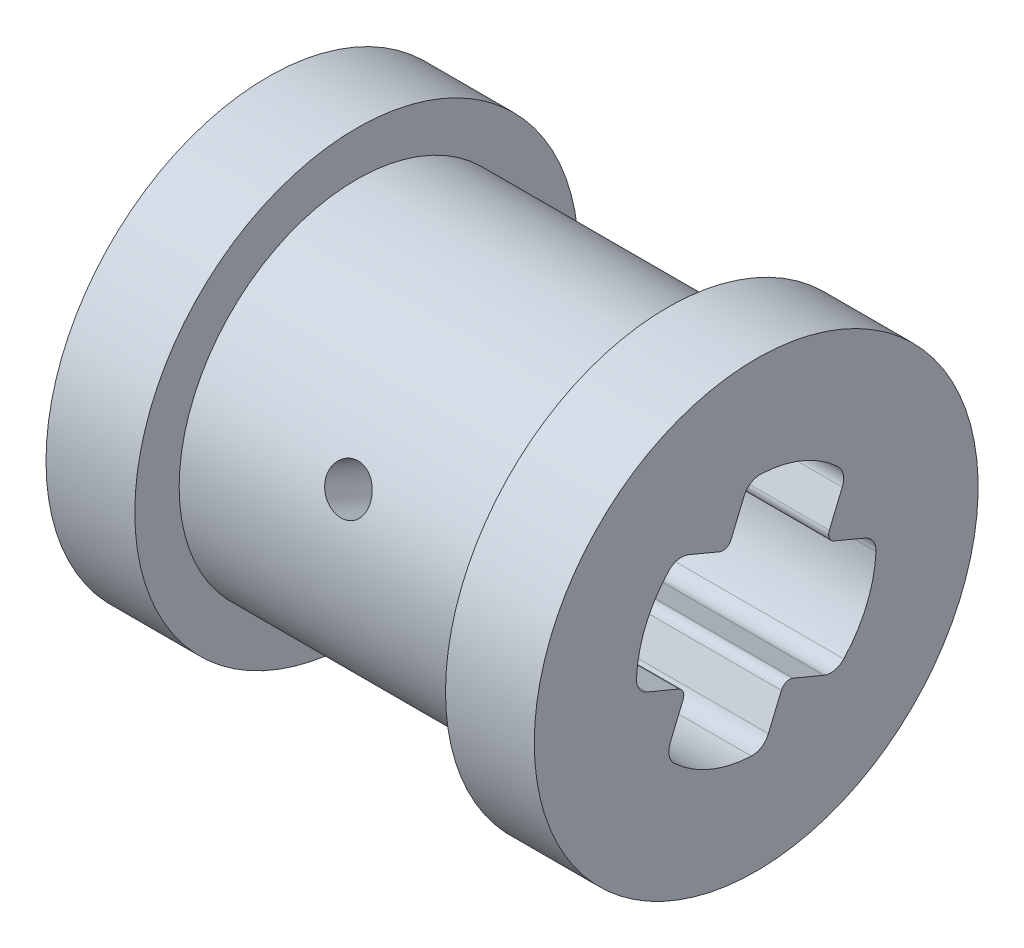
SolidWorks part; units mm, degrees
ref_plane "Front Plane" through (0, 0, 0) normal (0, 0, 1) x (1, 0, 0)
ref_plane "Top Plane" through (0, 0, 0) normal (0, 1, 0) x (1, 0, 0)
ref_plane "Right Plane" through (0, 0, 0) normal (1, 0, 0) x (0, 0, -1)
sketch "Sketch1" plane through (0, 0, 0) normal (0, 1, 0) x (1, 0, 0)
  line L0 (-3.5, -5) -> (-3.5, -4)
  line L1 (-5.5, 0) -> (5.5, 0)
  line L2 (-5.5, 0) -> (-5.5, -5)
  line L3 (-5.5, -5) -> (-3.5, -5)
  line L4 (5.5, 0) -> (5.5, -5)
  line L7 (-3.5, -4) -> (3.5, -4)
  line L8 (3.5, -4) -> (3.5, -5)
  line L9 (3.5, -5) -> (5.5, -5)
  point P10 (0, 0)
  dimension "D1" = 5
  dimension "D2" = 11
  dimension "D3" = 2
  dimension "D4" = 2
  dimension "D5" = 1
revolve "Revolve1" add sketch "Sketch1" angle 360 about L1
sketch "Sketch3" plane through (5.5, 0, 0) normal (1, 0, 0) x (0, 0, -1)
  line B0 (-1.3705, -0.9444) -> (-1.6623, -1.6422)
  line B1 (-0.0017, -2.3367) -> (0.2902, -1.6388)
  line B2 (0.9444, -1.3705) -> (1.6422, -1.6623)
  line B3 (-0.9444, 1.3705) -> (-1.6422, 1.6623)
  line B4 (-2.3367, 0.0017) -> (-1.6388, -0.2902)
  line B5 (0.0017, 2.3367) -> (-0.2902, 1.6388)
  line B6 (1.3705, 0.9444) -> (1.6623, 1.6422)
  line B7 (2.3367, -0.0017) -> (1.6388, 0.2902)
  arc B8 (-1.6623, -1.6422) -> (-1.6383, -1.7538) centre (-1.5701, -1.6808) ccw
  arc B9 (-1.6383, -1.7538) -> (-0.098, -2.398) centre (0, 0) ccw
  arc B10 (-0.098, -2.398) -> (-0.0017, -2.3367) centre (-0.0939, -2.2981) ccw
  arc B11 (1.6422, -1.6623) -> (1.7538, -1.6383) centre (1.6808, -1.5701) ccw
  arc B12 (0.9444, -1.3705) -> (0.2902, -1.6388) centre (0.7514, -1.8318) ccw
  arc B13 (-1.6422, 1.6623) -> (-1.7538, 1.6383) centre (-1.6808, 1.5701) ccw
  arc B14 (-2.398, 0.098) -> (-2.3367, 0.0017) centre (-2.2981, 0.0939) ccw
  arc B15 (-1.7538, 1.6383) -> (-2.398, 0.098) centre (0, 0) ccw
  arc B16 (-1.3705, -0.9444) -> (-1.6388, -0.2902) centre (-1.8318, -0.7514) ccw
  arc B17 (0.098, 2.398) -> (0.0017, 2.3367) centre (0.0939, 2.2981) ccw
  arc B18 (1.6383, 1.7538) -> (0.098, 2.398) centre (0, 0) ccw
  arc B19 (-0.9444, 1.3705) -> (-0.2902, 1.6388) centre (-0.7514, 1.8318) ccw
  arc B20 (1.6623, 1.6422) -> (1.6383, 1.7538) centre (1.5701, 1.6808) ccw
  arc B21 (1.3705, 0.9444) -> (1.6388, 0.2902) centre (1.8318, 0.7514) ccw
  arc B22 (2.398, -0.098) -> (2.3367, -0.0017) centre (2.2981, -0.0939) ccw
  arc B23 (1.7538, -1.6383) -> (2.398, -0.098) centre (0, 0) ccw
  arc B24 (0.1103, 2.6977) -> (-0.2751, 2.4524) centre (0.0939, 2.2981) ccw
  arc B25 (2.6977, -0.1103) -> (2.4524, 0.2751) centre (2.2981, -0.0939) ccw
  arc B26 (-0.1103, -2.6977) -> (0.2751, -2.4524) centre (-0.0939, -2.2981) ccw
  arc B27 (-2.6977, 0.1103) -> (-2.4524, -0.2751) centre (-2.2981, 0.0939) ccw
  line B28 (-0.2751, 2.4524) -> (-0.5669, 1.7546)
  line B29 (1.6472, 0.8286) -> (1.9391, 1.5264)
  line B30 (2.4524, 0.2751) -> (1.7546, 0.5669)
  line B31 (0.8286, -1.6472) -> (1.5264, -1.9391)
  line B32 (0.2751, -2.4524) -> (0.5669, -1.7546)
  line B33 (-1.6472, -0.8286) -> (-1.9391, -1.5264)
  line B34 (-2.4524, -0.2751) -> (-1.7546, -0.5669)
  line B35 (-0.8286, 1.6472) -> (-1.5264, 1.9391)
  circle B36 centre (0, 0) radius 5
  arc B37 (-0.8286, 1.6472) -> (-0.5669, 1.7546) centre (-0.7514, 1.8318) ccw
  arc B38 (1.8431, 1.9731) -> (0.1103, 2.6977) centre (0, 0) ccw
  arc B39 (1.9391, 1.5264) -> (1.8431, 1.9731) centre (1.5701, 1.6808) ccw
  arc B40 (1.6472, 0.8286) -> (1.7546, 0.5669) centre (1.8318, 0.7514) ccw
  arc B41 (1.9731, -1.8431) -> (2.6977, -0.1103) centre (0, 0) ccw
  arc B42 (1.5264, -1.9391) -> (1.9731, -1.8431) centre (1.6808, -1.5701) ccw
  arc B43 (0.8286, -1.6472) -> (0.5669, -1.7546) centre (0.7514, -1.8318) ccw
  arc B44 (-1.8431, -1.9731) -> (-0.1103, -2.6977) centre (0, 0) ccw
  arc B45 (-1.9391, -1.5264) -> (-1.8431, -1.9731) centre (-1.5701, -1.6808) ccw
  arc B46 (-1.6472, -0.8286) -> (-1.7546, -0.5669) centre (-1.8318, -0.7514) ccw
  arc B47 (-1.9731, 1.8431) -> (-2.6977, 0.1103) centre (0, 0) ccw
  arc B48 (-1.5264, 1.9391) -> (-1.9731, 1.8431) centre (-1.6808, 1.5701) ccw
sketch_block_instance "shaft-1"
sketch_block "shaft" parameters "D1"=0.1
extrude "Cut-Extrude1" cut sketch "Sketch3" against normal through all
ref_plane "Plane1" through (0, 0.0772, 0.1845) normal (0, -0.3858, -0.9226) x (-1, 0, 0)
sketch "Sketch4" plane through (0, 0.0772, 0.1845) normal (0, -0.3858, -0.9226) x (-1, 0, 0)
  circle A0 centre (0, 0) radius 0.5
  dimension "D1" = 1
extrude "Cut-Extrude2" cut sketch "Sketch4" against normal through all both and the other way through all
